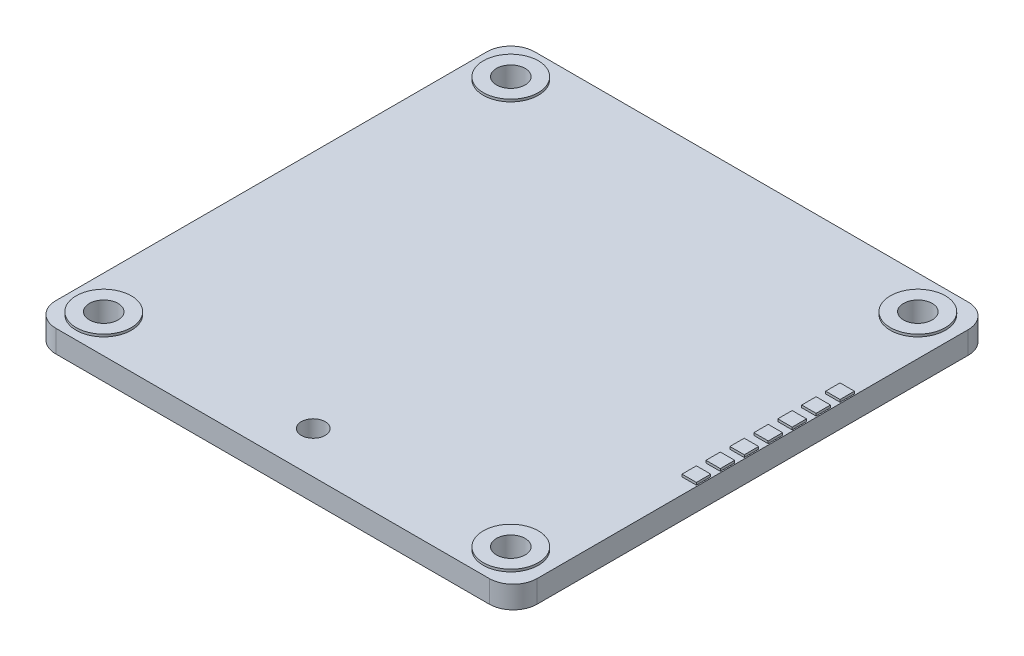
SolidWorks part; units mm, degrees
ref_plane "Front Plane" through (0, 0, 0) normal (0, 0, 1) x (1, 0, 0)
ref_plane "Top Plane" through (0, 0, 0) normal (0, 1, 0) x (1, 0, 0)
ref_plane "Right Plane" through (0, 0, 0) normal (1, 0, 0) x (0, 0, -1)
sketch "Sketch1" plane through (0, 0, 0) normal (0, 1, 0) x (1, 0, 0)
  line L1 (0, 0) -> (51.054, 0)
  line L2 (0, 0) -> (0, 50.8)
  line L3 (0, 50.8) -> (51.054, 50.8)
  line L4 (51.054, 0) -> (51.054, 50.8)
  dimension "D1" = 50.8
  dimension "D2" = 51.054
extrude "Boss-Extrude1" add sketch "Sketch1" along normal blind 2.3622
sketch "Sketch5" plane through (0, 2.3622, 0) normal (0, 1, 0) x (1, 0, 0)
  line L0 (0, 0) -> (51.054, 0) construction
  line L1 (0, 50.8) -> (0, 0) construction
  circle A0 centre (3.81, 3.81) radius 2.921
  dimension "D1" = 3.81
  dimension "D2" = 3.81
extrude "Boss-Extrude3" add sketch "Sketch5" along normal blind 0.254
sketch "Sketch2" plane through (0, 2.3622, 0) normal (0, 1, 0) x (1, 0, 0)
  line L0 (0, 50.8) -> (0, 0) construction
  line L1 (0, 0) -> (51.054, 0) construction
  circle A0 centre (3.81, 3.81) radius 1.524
  dimension "D1" = 3.81
  dimension "D2" = 3.81
extrude "Cut-Extrude1" cut sketch "Sketch2" against normal through all both and the other way through all
pattern_linear "LPattern1" count 2 spacing 43.18 along (0, 0, -1) count 2 spacing 43.18 along (1, 0, 0) of "Cut-Extrude1", "Boss-Extrude3"
fillet "Fillet1" radius 2.54 4 edges at (0, 1.1811, -50.8) (0, 1.1811, 0) (51.054, 1.1811, 0) (51.054, 1.1811, -50.8)
sketch "Sketch3" plane through (0, 2.3622, 0) normal (0, 1, 0) x (1, 0, 0)
  line L0 (2.54, 0) -> (48.514, 0) construction
  line L1 (0, 48.26) -> (0, 2.54) construction
  circle A0 centre (25.4, 4.4432) radius 1.27
  point P2 (25.527, 0)
  dimension "D1" = 4.445
  dimension "D3" = 2.54
  dimension "D2" = 25.4
extrude "Cut-Extrude2" cut sketch "Sketch3" against normal through all
sketch "Sketch6" plane through (0, 2.3622, 0) normal (0, 1, 0) x (1, 0, 0)
  line L0 (49.403, 34.798) -> (50.927, 34.798)
  line L1 (49.403, 34.798) -> (49.403, 36.322)
  line L2 (50.927, 34.798) -> (50.927, 36.322)
  line L3 (49.403, 36.322) -> (50.927, 36.322)
  line L4 (49.403, 34.798) -> (50.927, 36.322) construction
  line L5 (50.927, 34.798) -> (49.403, 36.322) construction
  line L6 (2.54, 0) -> (48.514, 0) construction
  point P1 (50.165, 35.56)
  dimension "D1" = 35.56
  dimension "D2" = 1.524
extrude "Boss-Extrude4" add sketch "Sketch6" along normal blind 0.254
pattern_linear "LPattern2" count 7 spacing 2.54 along (0, 0, 1) of "Boss-Extrude4"
